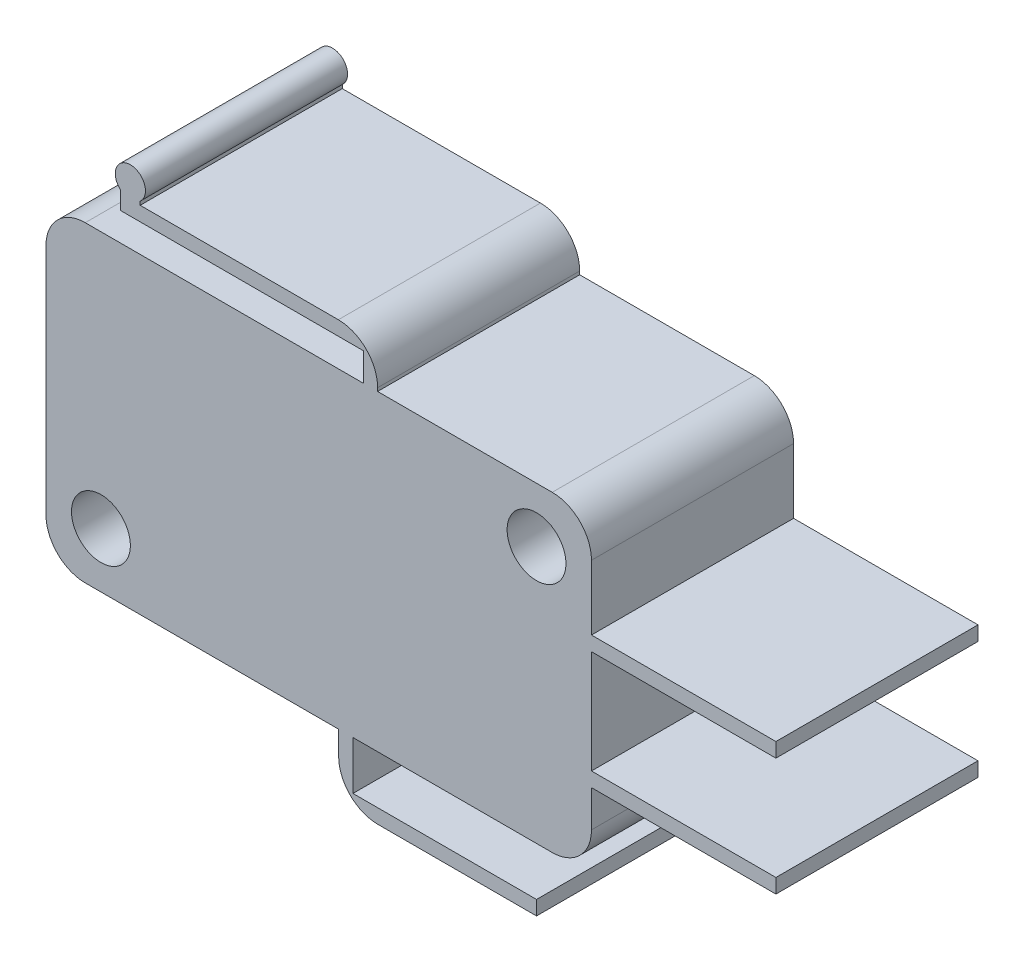
SolidWorks part; units mm, degrees
ref_plane "Ön Düzlem" through (0, 0, 0) normal (0, 0, 1) x (1, 0, 0)
ref_plane "Üst Düzlem" through (0, 0, 0) normal (0, 1, 0) x (1, 0, 0)
ref_plane "Sağ Düzlem" through (0, 0, 0) normal (1, 0, 0) x (0, 0, -1)
sketch "Çizim1" plane through (0, 0, 0) normal (0, 0, 1) x (1, 0, 0)
  line L0 (13.9, -4.0848) -> (22.3306, -4.0848)
  line L1 (-13.9, 7.95) -> (2.27, 7.95)
  line L2 (-13.9, 7.95) -> (-13.9, -7.95)
  line L3 (-13.9, -7.95) -> (1.0146, -7.95)
  line L4 (13.9, 7.95) -> (13.9, 2.6501)
  line L5 (-13.9, 7.95) -> (13.9, -7.95) construction
  line L6 (-13.9, -7.95) -> (13.9, 7.95) construction
  line L7 (22.3306, -4.0848) -> (23.3, -4.0848)
  line L8 (23.3, -3.91) -> (23.3, -3.6084)
  line L9 (23.3, -4.0848) -> (23.3, -3.91)
  line L10 (22.3306, -3.3499) -> (13.9, -3.3499)
  line L11 (22.3306, -3.3499) -> (23.3, -3.3499)
  line L12 (23.3, -3.3499) -> (23.3, -3.6084)
  line L13 (22.3306, 2.6501) -> (13.9, 2.6501)
  line L14 (13.9, 1.9152) -> (22.3306, 1.9152)
  line L15 (22.3306, 1.9152) -> (23.3, 1.9152)
  line L16 (22.3306, 2.6501) -> (23.3, 2.6501)
  line L17 (23.3, 2.6501) -> (23.3, 2.3916)
  line L18 (23.3, 2.09) -> (23.3, 2.3916)
  line L19 (23.3, 1.9152) -> (23.3, 2.09)
  line L20 (13.9, 1.9152) -> (13.9, -3.3499)
  line L21 (13.9, -4.0848) -> (13.9, -7.95)
  line L22 (1.7446, -7.95) -> (1.7446, -10.42)
  line L23 (1.7446, -10.42) -> (11.1, -10.42)
  line L24 (11.1, -10.42) -> (11.1, -11.15)
  line L25 (11.1, -11.15) -> (1.0146, -11.15)
  line L26 (1.0146, -11.15) -> (1.0146, -7.95)
  line L27 (1.7446, -7.95) -> (13.9, -7.95)
  line L28 (3, 7.95) -> (3, 10.1168)
  line L29 (3, 10.1168) -> (-9.1, 10.1168)
  line L30 (3, 7.95) -> (13.9, 7.95)
  line L31 (-9.1, 9.3868) -> (2.27, 9.3868)
  line L32 (2.27, 9.3868) -> (2.27, 7.95)
  line L33 (-9.1, 10.1168) -> (-9.1, 10.8868)
  line L34 (-9.1, 9.3868) -> (-10.1, 9.3868)
  line L35 (-10.1, 9.3868) -> (-10.1, 10.8868)
  circle A0 centre (11.1, 5.15) radius 1.5
  circle A1 centre (-11.1, -5.15) radius 1.5
  arc A2 (-9.1, 10.8868) -> (-10.1, 10.8868) centre (-9.6, 10.8868) ccw
  point P0 (0, 0)
  point P32 (1.7446, -9.185)
  point P38 (-9.1, 10.5018)
  dimension "D3" = 3
  dimension "D4" = 3
  dimension "D20" = 1
  dimension "D1" = 27.8
  dimension "D2" = 15.9
  dimension "D5" = 2.8
  dimension "D6" = 2.8
  dimension "D7" = 2.8
  dimension "D8" = 2.8
  dimension "D9" = 9.4
  dimension "D10" = 0.7349
  dimension "D12" = 22.2
  dimension "D13" = 19.1
  dimension "D14" = 0.73
  dimension "D15" = 0.73
  dimension "D16" = 8.1
  dimension "D17" = 0.73
  dimension "D18" = 0.73
  dimension "D19" = 1
  dimension "D21" = 1.5
  dimension "D22" = 20.7
  dimension "D11" = 2
extrude "Yükseklik-Ekstrüzyon1" add sketch "Çizim1" along normal blind 10.3
fillet "Radyus2" radius 2 6 edges at (1.0146, -11.15, 5.15) (3, 10.1168, 5.15) (-13.9, -7.95, 5.15) (-13.9, 7.95, 5.15) (13.9, -7.95, 5.15) (13.9, 7.95, 5.15)
sketch "Çizim4" plane through (0, 0, 10.3) normal (0, 0, 1) x (1, 0, 0)
  circle A0 centre (-9.6, 10.8868) radius 0.77
extrude "Yükseklik-Ekstrüzyon2" add sketch "Çizim4" against normal blind 10.3
